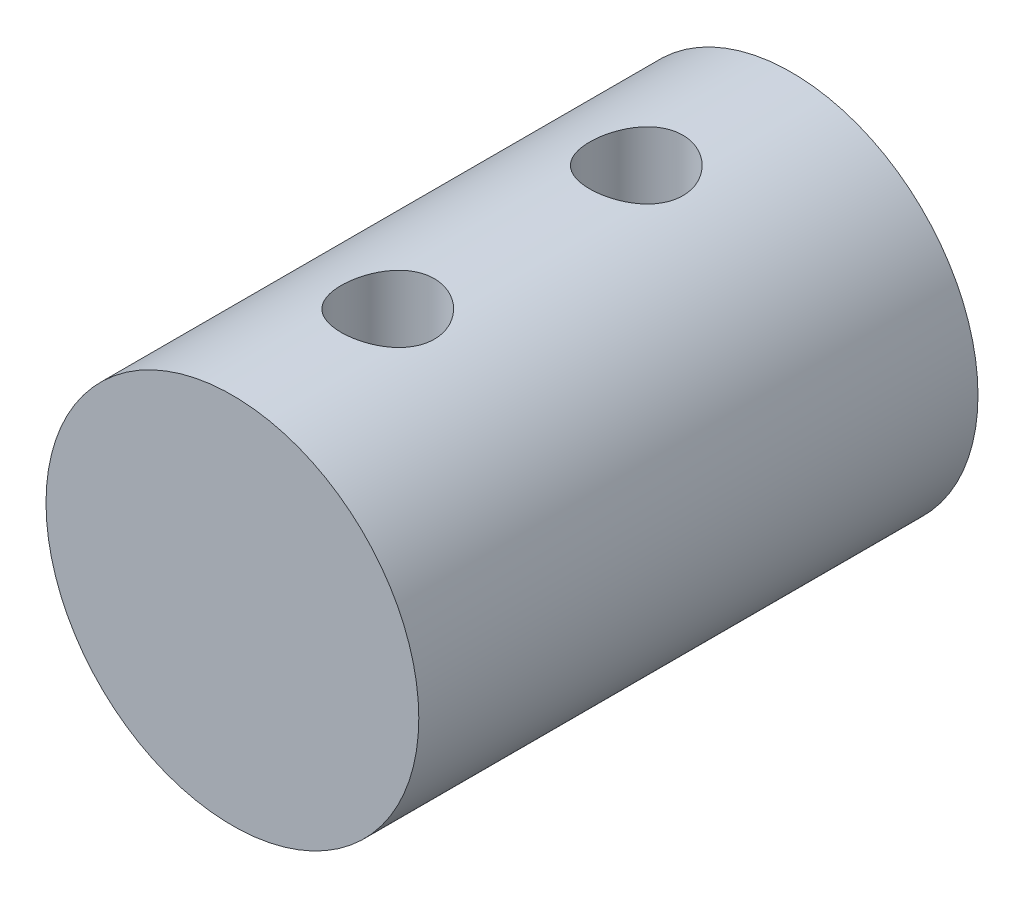
SolidWorks part; units mm, degrees
material "ABS"
ref_plane "Front" through (0, 0, 0) normal (0, 0, 1) x (1, 0, 0)
ref_plane "Top" through (0, 0, 0) normal (0, 1, 0) x (1, 0, 0)
ref_plane "Right" through (0, 0, 0) normal (1, 0, 0) x (0, 0, -1)
sketch "草图1" plane through (0, 0, 0) normal (0, 0, 1) x (1, 0, 0)
  circle A0 centre (0, 0) radius 6
  dimension "D1" = 12
extrude "凸台-拉伸1" add sketch "草图1" along normal blind 18
sketch "草图2" plane through (0, 0, 0) normal (0, 1, 0) x (1, 0, 0)
  line L0 (6, -9) -> (-11.2059, -9) construction
  line L1 (6, -18) -> (6, 0) construction
  line L2 (6, 0) -> (-6, 0) construction
  circle A0 centre (0, -5) radius 1.5
  circle A1 centre (0, -13) radius 1.5
  dimension "D1" = 5
  dimension "D2" = 3
extrude "切除-拉伸1" cut sketch "草图2" against normal through all both and the other way through all
